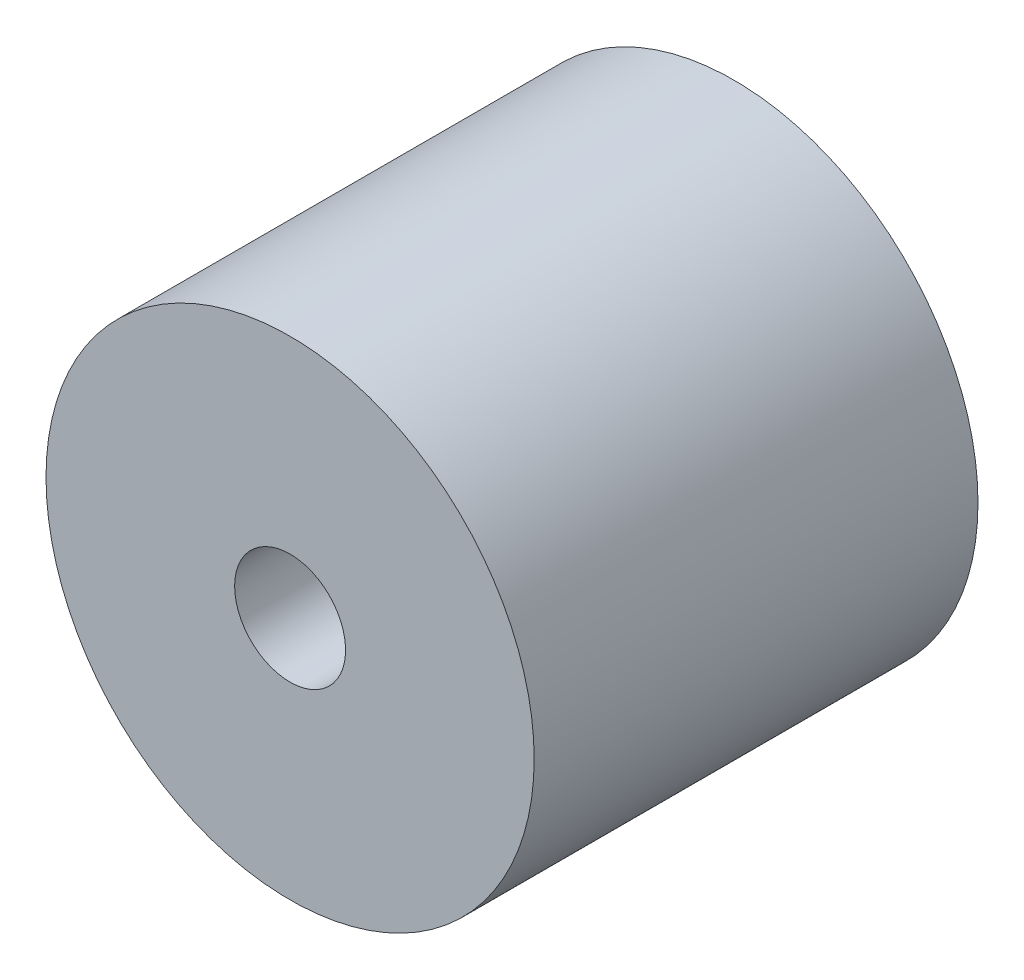
SolidWorks part; units mm, degrees
ref_plane "前视基准面" through (0, 0, 0) normal (0, 0, 1) x (1, 0, 0)
ref_plane "上视基准面" through (0, 0, 0) normal (0, 1, 0) x (1, 0, 0)
ref_plane "右视基准面" through (0, 0, 0) normal (1, 0, 0) x (0, 0, -1)
sketch "草图1" plane through (0, 0, 0) normal (0, 0, 1) x (1, 0, 0)
  circle A0 centre (0, 0) radius 11
  dimension "D1" = 22
extrude "凸台-拉伸1" add sketch "草图1" along normal blind 20
sketch "草图3" plane through (0, 0, 0) normal (0, 0, -1) x (-1, 0, 0)
  circle A0 centre (0, 0) radius 2.5
  dimension "D1" = 5
extrude "切除-拉伸2" cut sketch "草图3" against normal through all
